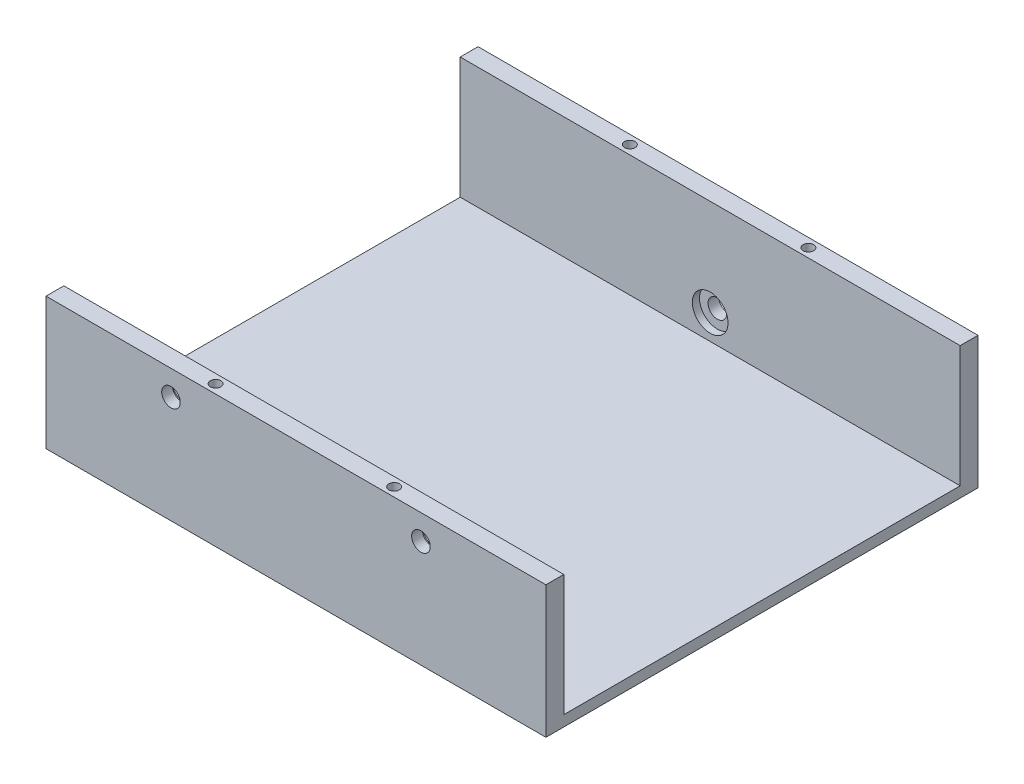
SolidWorks part; units mm, degrees
ref_plane "前视基准面" through (0, 0, 0) normal (0, 0, 1) x (1, 0, 0)
ref_plane "上视基准面" through (0, 0, 0) normal (0, 1, 0) x (1, 0, 0)
ref_plane "右视基准面" through (0, 0, 0) normal (1, 0, 0) x (0, 0, -1)
other "Configuration Table"
sketch "草图1" plane through (0, 0, 0) normal (0, 1, 0) x (1, 0, 0)
  line L1 (0, 0) -> (150, 0)
  line L2 (0, 0) -> (0, 123)
  line L3 (0, 123) -> (150, 123)
  line L4 (150, 0) -> (150, 123)
  line L11 (19, 61.5) -> (19, 102.5)
  line L12 (19, 61.5) -> (19, 20.5)
  line L14 (141, 61.5) -> (141, 102.5)
  line L15 (141, 61.5) -> (141, 20.5)
  circle A0 centre (19, 102.5) radius 1.5
  circle A1 centre (19, 20.5) radius 1.5
  circle A2 centre (141, 20.5) radius 1.5
  circle A3 centre (141, 102.5) radius 1.5
extrude "凸台-拉伸1" add sketch "草图1" along normal blind 3
sketch "草图2" plane through (0, 3, 0) normal (0, 1, 0) x (1, 0, 0)
  line L0 (150, 0) -> (150, 123) construction
  line L1 (0, 123) -> (150, 123)
  line L2 (0, 123) -> (0, 117)
  line L3 (0, 117) -> (150, 117)
  line L4 (150, 123) -> (150, 117)
extrude "凸台-拉伸2" add sketch "草图2" along normal blind 17
sketch "草图3" plane through (0, 3, 0) normal (0, 1, 0) x (1, 0, 0)
  line L1 (150, 0) -> (75, 0)
  line L2 (150, 0) -> (150, 6)
  line L3 (150, 6) -> (75, 6)
  line L4 (75, 0) -> (75, 6)
extrude "凸台-拉伸3" add sketch "草图3" along normal blind 37
sketch "草图4" plane through (0, 3, 0) normal (0, 1, 0) x (1, 0, 0)
  line L1 (0, 117) -> (150, 117)
  line L2 (0, 117) -> (0, 6)
  line L3 (0, 6) -> (150, 6)
  line L4 (150, 117) -> (150, 6)
extrude "凸台-拉伸4" add sketch "草图4" against normal blind 3
sketch "草图6" plane through (0, 0, 0) normal (0, -1, 0) x (1, 0, 0)
  line L2 (150, 0) -> (140, 0)
  line L3 (150, 0) -> (150, -123)
  line L4 (150, -123) -> (140, -123)
  line L5 (140, 0) -> (140, -123)
extrude "切除-拉伸1" cut sketch "草图6" against normal blind 50
sketch "草图7" plane through (0, 3, 0) normal (0, 1, 0) x (1, 0, 0)
  line L9 (75, 6) -> (0, 6)
  line L10 (75, 6) -> (75, 0)
  line L11 (75, 0) -> (0, 0)
  line L12 (0, 6) -> (0, 0)
  line L13 (0, 6) -> (3, 6)
  line L14 (0, 6) -> (0, 107)
  line L15 (0, 107) -> (3, 107)
  line L16 (3, 6) -> (3, 107)
  line M13 (0, 117) -> (0, 0)
extrude "凸台-拉伸5" add sketch "草图7" along normal blind 17 contours L9 L16 L15 M13
sketch "草图9" plane through (0, 3, 0) normal (0, 1, 0) x (1, 0, 0)
  line L1 (0, 0) -> (75, 0)
  line L2 (0, 0) -> (0, 6)
  line L3 (0, 6) -> (75, 6)
  line L4 (75, 0) -> (75, 6)
extrude "凸台-拉伸6" add sketch "草图9" along normal blind 37
sketch "草图11" plane through (0, 0, -6) normal (0, 0, -1) x (-1, 0, 0)
  line L2 (0, 40) -> (0, 20) construction
  line L3 (-70, 30) -> (0, 30)
  line L4 (-70, 30) -> (-140, 30)
  circle A0 centre (-105, 30) radius 2.6
  circle A1 centre (-35, 30) radius 2.6
extrude "切除-拉伸2" cut sketch "草图11" against normal blind 37 contours L4 A0 | L4 A0 | L3 A1 | L3 A1
sketch "草图12" plane through (0, 0, -6) normal (0, 0, -1) x (-1, 0, 0)
  circle A0 centre (-105, 30) radius 5
  circle A1 centre (-35, 30) radius 5
extrude "切除-拉伸3" cut sketch "草图12" against normal blind 3
sketch "草图13" plane through (0, 0, -117) normal (0, 0, 1) x (1, 0, 0)
  line L0 (140, 0) -> (140, 20)
  line L1 (140, 10) -> (0, 10)
  line L2 (0, 20) -> (0, 0) construction
  circle A0 centre (70, 10) radius 2.6
extrude "切除-拉伸5" cut sketch "草图13" against normal blind 6 contours L1 A0 | L1 A0
sketch "草图14" plane through (0, 0, -117) normal (0, 0, 1) x (1, 0, 0)
  circle A0 centre (70, 10) radius 5
extrude "切除-拉伸6" cut sketch "草图14" against normal blind 3
sketch "草图15" plane through (0, 0, 0) normal (0, 0, 1) x (1, 0, 0)
  line L0 (140, 40) -> (140, 0) construction
  line L1 (0, 40) -> (140, 40)
  line L2 (0, 40) -> (0, 37)
  line L3 (0, 37) -> (140, 37)
  line L4 (140, 40) -> (140, 37)
extrude "切除-拉伸7" cut sketch "草图15" against normal blind 6
sketch "草图17" plane through (0, 20, 0) normal (0, 1, 0) x (1, 0, 0)
  line L1 (0, 123) -> (140, 123)
  line L2 (0, 123) -> (0, 117)
  line L3 (0, 117) -> (140, 117)
  line L4 (140, 123) -> (140, 117)
  line L5 (0, 6) -> (3, 6)
  line L6 (0, 6) -> (0, 107)
  line L7 (0, 107) -> (3, 107)
  line L8 (3, 6) -> (3, 107)
extrude "凸台-拉伸7" add sketch "草图17" along normal blind 17
sketch "草图19" plane through (0, 37, 0) normal (0, 1, 0) x (1, 0, 0)
  line L0 (140, 117) -> (140, 123) construction
  line L1 (0, 123) -> (140, 123)
  line L2 (0, 123) -> (0, 122)
  line L3 (0, 122) -> (140, 122)
  line L4 (140, 123) -> (140, 122)
extrude "切除-拉伸10" cut sketch "草图19" against normal blind 50
sketch "草图20" plane through (0, 37, 0) normal (0, 1, 0) x (1, 0, 0)
  line L0 (140, 6) -> (140, 0) construction
  line L1 (0, 0) -> (140, 0)
  line L2 (0, 0) -> (0, 1)
  line L3 (0, 1) -> (140, 1)
  line L4 (140, 0) -> (140, 1)
extrude "切除-拉伸11" cut sketch "草图20" against normal blind 50
sketch "草图21" plane through (0, 37, 0) normal (0, 1, 0) x (1, 0, 0)
  line L1 (0, 107) -> (3, 107)
  line L2 (0, 107) -> (0, 6)
  line L3 (0, 6) -> (3, 6)
  line L4 (3, 107) -> (3, 6)
extrude "切除-拉伸12" cut sketch "草图21" against normal blind 34
sketch "草图22" plane through (0, 37, 0) normal (0, 1, 0) x (1, 0, 0)
  line L0 (0, 1) -> (0, 6)
  line L1 (70, 3.5) -> (95, 3.5)
  line L3 (70, 119.5) -> (95, 119.5)
  line L4 (0, 122) -> (140, 122) construction
  line L5 (70, 122) -> (70, 117)
  line L6 (0, 117) -> (140, 117) construction
  line L7 (70, 119.5) -> (45, 119.5)
  line L8 (70, 3.5) -> (70, 1)
  line L9 (140, 1) -> (0, 1) construction
  line L10 (70, 3.5) -> (45, 3.5)
  circle A0 centre (95, 119.5) radius 1.48
  circle A1 centre (45, 119.5) radius 1.48
  circle A2 centre (45, 3.5) radius 1.48
  circle A3 centre (95, 3.5) radius 1.48
extrude "切除-拉伸13" cut sketch "草图22" against normal blind 10
sketch "草图23" plane through (0, 0, -120) normal (0, 0, 1) x (1, 0, 0)
  circle A0 centre (70, 10) radius 2.6
  circle A1 centre (70, 10) radius 5
extrude "凸台-拉伸8" add sketch "草图23" along normal blind 1
sketch "草图24" plane through (0, 0, -3) normal (0, 0, -1) x (-1, 0, 0)
  circle A0 centre (-105, 30) radius 2.6
  circle A1 centre (-105, 30) radius 5
  circle A2 centre (-35, 30) radius 2.6
  circle A3 centre (-35, 30) radius 5
extrude "凸台-拉伸9" add sketch "草图24" along normal blind 1
sketch "草图25" plane through (0, 37, 0) normal (0, 1, 0) x (1, 0, 0)
  line L0 (45, 119.5) -> (45, 3.5)
  line L1 (45, 119.5) -> (95, 119.5)
